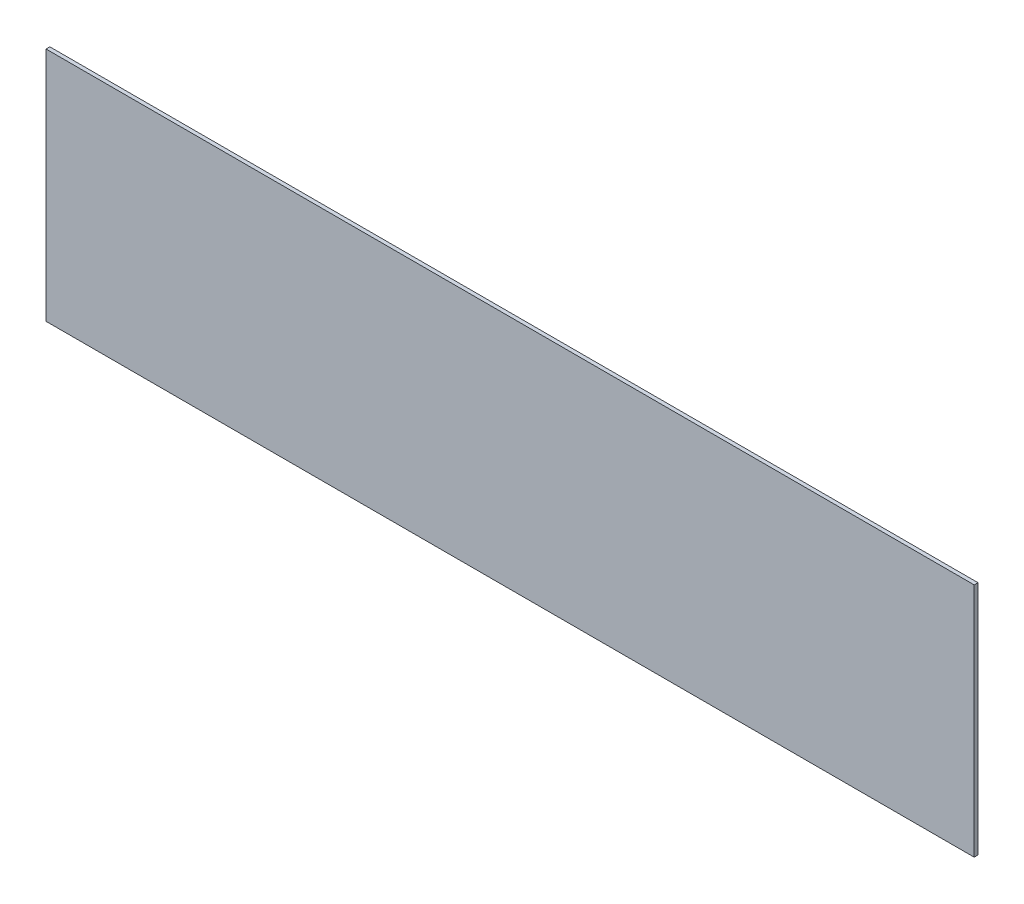
SolidWorks part; units mm, degrees
material "Бальса"
ref_plane "Спереди" through (0, 0, 0) normal (0, 0, 1) x (1, 0, 0)
ref_plane "Сверху" through (0, 0, 0) normal (0, 1, 0) x (1, 0, 0)
ref_plane "Справа" through (0, 0, 0) normal (1, 0, 0) x (0, 0, -1)
sketch "Эскиз1" plane through (0, 0, 0) normal (0, 0, 1) x (1, 0, 0)
  line L1 (0, 0) -> (2440, 0)
  line L2 (0, 0) -> (0, 620)
  line L3 (0, 620) -> (2440, 620)
  line L4 (2440, 0) -> (2440, 620)
  line L8 (2440, 950) -> (2440, 620) construction
  line L9 (0, 950) -> (2440, 950) construction
  line L10 (2440, 950) -> (2440, 900) construction
  dimension "D2" = 620
extrude "Бобышка-Вытянуть1" add sketch "Эскиз1" along normal blind 10
